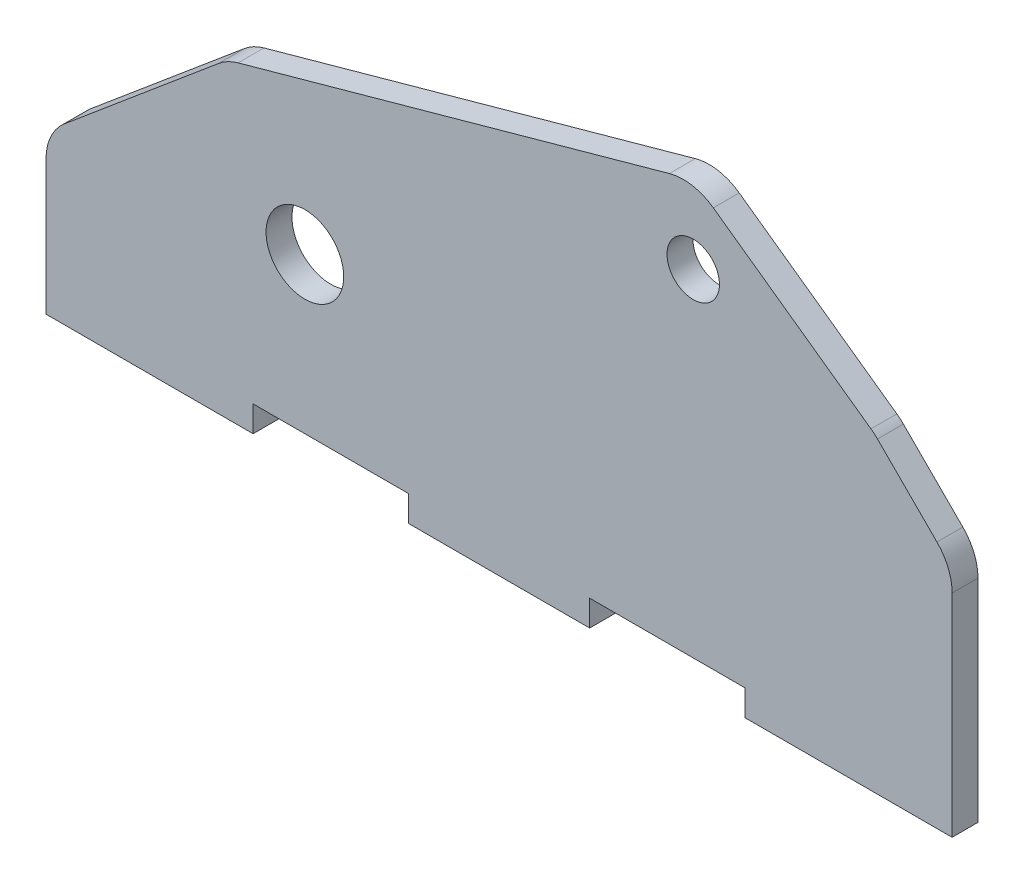
SolidWorks part; units mm, degrees
ref_plane "Plan de face" through (0, 0, 0) normal (0, 0, 1) x (1, 0, 0)
ref_plane "Plan de dessus" through (0, 0, 0) normal (0, 1, 0) x (1, 0, 0)
ref_plane "Plan de droite" through (0, 0, 0) normal (1, 0, 0) x (0, 0, -1)
sketch "Esquisse1" plane through (0, 0, 0) normal (0, 0, 1) x (1, 0, 0)
  line L0 (0, 0) -> (350, 0) construction
  line L1 (350, 0) -> (350, 90)
  line L2 (350, 90) -> (320, 120)
  line L3 (320, 120) -> (250, 170)
  line L4 (250, 170) -> (70, 120)
  line L5 (0, 90) -> (0, 0) construction
  line L6 (0, 90) -> (350, 90) construction
  line L7 (70, 120) -> (0, 90) construction
  line L8 (70, 120) -> (70, 90) construction
  line L9 (250, 170) -> (250, 90) construction
  line L10 (320, 120) -> (250, 120) construction
  line L11 (320, 120) -> (320, 90) construction
  line L12 (0, 0) -> (80, 0)
  line L13 (80, 0) -> (80, 10)
  line L14 (80, 10) -> (140, 10)
  line L15 (140, 10) -> (140, 0)
  line L16 (140, 0) -> (210, 0)
  line L17 (210, 0) -> (210, 10)
  line L18 (210, 10) -> (270, 10)
  line L19 (270, 10) -> (270, 0)
  line L20 (270, 0) -> (350, 0)
  line L21 (175, 0) -> (175, 90) construction
  line L22 (70, 120) -> (250, 120) construction
  line L23 (0, 10) -> (350, 10) construction
  line L24 (70, 120) -> (0, 61.263)
  line L25 (0, 0) -> (0, 61.263)
  circle A0 centre (100, 70) radius 15
  circle A3 centre (250, 140) radius 10.125
  dimension "D6" = 30
  dimension "D7" = 30
  dimension "D8" = 80
  dimension "D5" = 350
  dimension "D12" = 20.25
  dimension "D3" = 30
  dimension "D1" = 90
  dimension "D2" = 10
  dimension "D4" = 100
  dimension "D9" = 60
  dimension "D10" = 60
  dimension "D11" = 70
  dimension "D13" = 100
  dimension "D14" = 150
  dimension "D15" = 70
  dimension "D16" = 50
  dimension "D17" = 30
  dimension "D18" = 50
extrude "Boss.-Extru.1" add sketch "Esquisse1" along normal blind 10
fillet "Congé1" radius 20 5 edges at (350, 90, 5) (320, 120, 5) (250, 170, 5) (0, 61.263, 5) (70, 120, 5)
